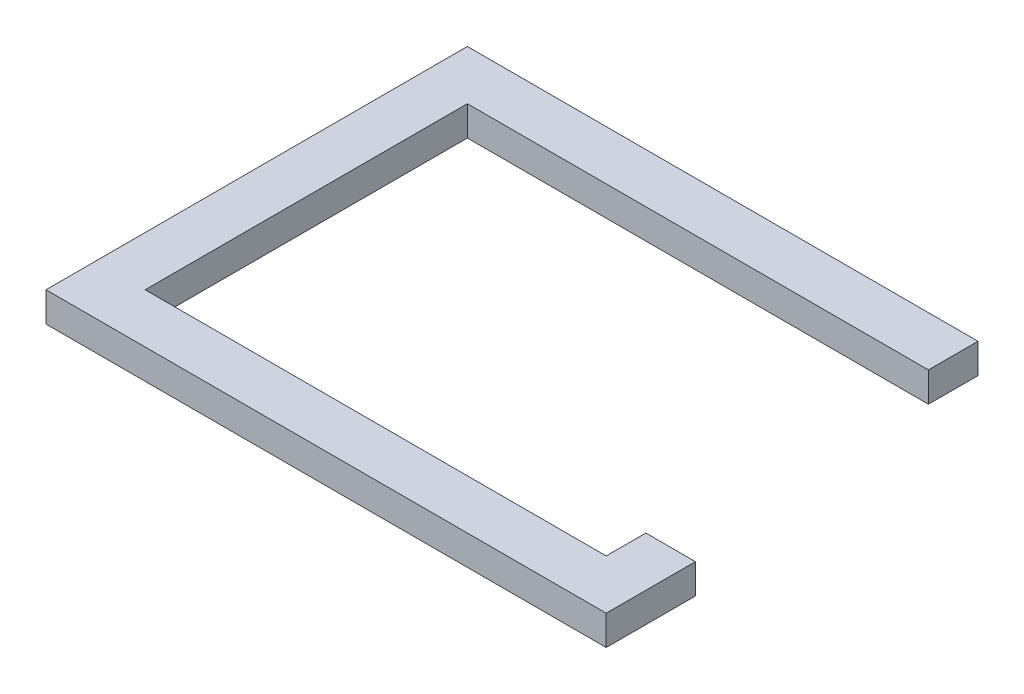
SolidWorks part; units mm, degrees
ref_plane "Front Plane" through (0, 0, 0) normal (0, 0, 1) x (1, 0, 0)
ref_plane "Top Plane" through (0, 0, 0) normal (0, 1, 0) x (1, 0, 0)
ref_plane "Right Plane" through (0, 0, 0) normal (1, 0, 0) x (0, 0, -1)
sketch "Sketch1" plane through (0, 0, 0) normal (0, 1, 0) x (1, 0, 0)
  line L17 (0, 0) -> (51.5, 0)
  line L18 (51.5, 0) -> (51.5, -5)
  line L19 (51.5, -5) -> (5, -5)
  line L20 (5, -5) -> (5, -37.5)
  line L21 (5, -37.5) -> (51.5, -37.5)
  line L22 (51.5, -37.5) -> (51.5, -33.5)
  line L23 (51.5, -33.5) -> (56.5, -33.5)
  line L24 (56.5, -33.5) -> (56.5, -42.5)
  line L25 (56.5, -42.5) -> (0, -42.5)
  line L26 (0, -42.5) -> (0, 0)
  dimension "D1" = 32.5
  dimension "D2" = 5
  dimension "D3" = 5
  dimension "D4" = 5
  dimension "D5" = 5
  dimension "D6" = 51.5
  dimension "D7" = 56.5
  dimension "D8" = 4
extrude "Boss-Extrude1" add sketch "Sketch1" along normal blind 3
